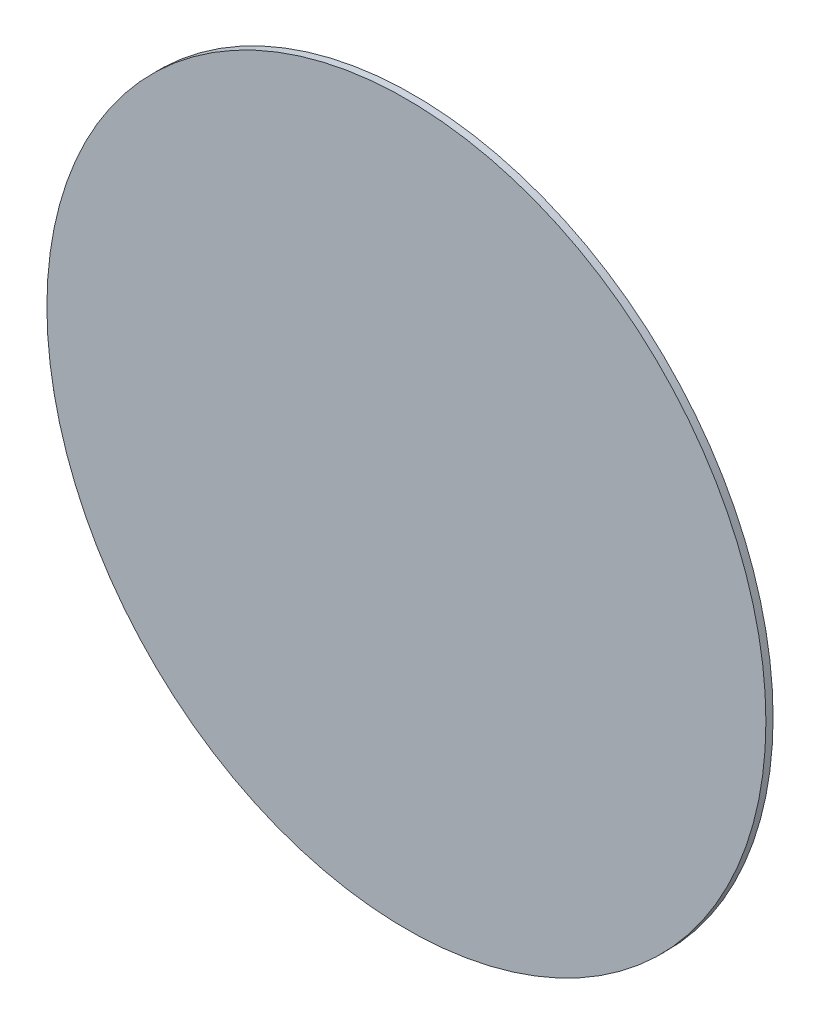
SolidWorks part; units mm, degrees
ref_plane "前视基准面" through (0, 0, 0) normal (0, 0, 1) x (1, 0, 0)
ref_plane "上视基准面" through (0, 0, 0) normal (0, 1, 0) x (1, 0, 0)
ref_plane "右视基准面" through (0, 0, 0) normal (1, 0, 0) x (0, 0, -1)
sketch "草图1" plane through (0, 0, 0) normal (0, 0, 1) x (1, 0, 0)
  circle A0 centre (0, 0) radius 500
  dimension "D1" = 1000
extrude "凸台-拉伸1" add sketch "草图1" along normal blind 10
